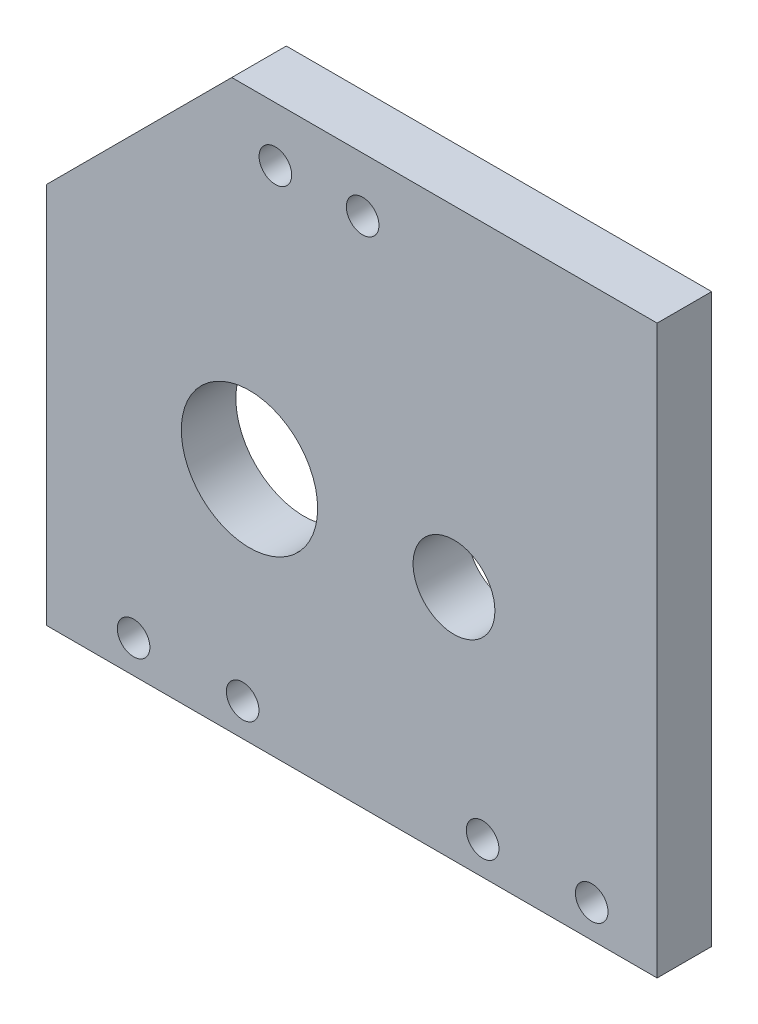
SolidWorks part; units mm, degrees
ref_plane "Front Plane" through (0, 0, 0) normal (0, 0, 1) x (1, 0, 0)
ref_plane "Top Plane" through (0, 0, 0) normal (0, 1, 0) x (1, 0, 0)
ref_plane "Right Plane" through (0, 0, 0) normal (1, 0, 0) x (0, 0, -1)
sketch "Sketch1" plane through (0, 0, 0) normal (0, 0, 1) x (1, 0, 0)
  line L1 (35.56, -33.02) -> (-35.56, -33.02)
  line L2 (35.56, -33.02) -> (35.56, 33.02)
  line L3 (35.56, 33.02) -> (-35.56, 33.02)
  line L4 (-35.56, -33.02) -> (-35.56, 33.02)
  line L5 (35.56, -33.02) -> (-35.56, 33.02) construction
  line L6 (35.56, 33.02) -> (-35.56, -33.02) construction
  circle A2 centre (-11.9062, -5.4381) radius 7.9375
  circle A3 centre (11.9062, -5.4381) radius 4.7625
  point P0 (0, 0)
  dimension "D11" = 9.525
  dimension "D12" = 15.875
  dimension "D1" = 71.12
  dimension "D2" = 66.04
  dimension "D9" = 5.4381
  dimension "D10" = 5.4381
  dimension "D13" = 11.9062
  dimension "D14" = 11.9062
extrude "Boss-Extrude1" add sketch "Sketch1" along normal blind 6.35
hole_wizard "#6 Clearance Hole1" positions "Sketch2" profile "Sketch3" hole size "#6" standard "ANSI Inch" end condition through all
sketch "Sketch2" plane through (0, 0, 6.35) normal (0, 0, 1) x (1, 0, 0)
  line L0 (-25.4, -29.21) -> (-12.7, -29.21)
  line L2 (15.24, -29.21) -> (27.94, -29.21)
  line L4 (-35.56, -33.02) -> (35.56, -33.02) construction
  line L5 (-35.56, 33.02) -> (-35.56, -33.02) construction
  point P0 (-25.4, -29.21)
  point P2 (-12.7, -29.21)
  point P4 (15.24, -29.21)
  point P6 (27.94, -29.21)
  dimension "D1" = 12.7
  dimension "D2" = 12.7
  dimension "D3" = 3.81
  dimension "D4" = 3.81
  dimension "D5" = 10.16
  dimension "D6" = 27.94
sketch "Sketch3" plane through (-25.4, -29.21, 6.35) normal (1, 0, 0) x (0, -1, 0)
  line L0 (0, 0) -> (0, 6.35)
  line L1 (0, 6.35) -> (1.8986, 6.35)
  line L2 (1.8986, 6.35) -> (1.8986, 0)
  line L5 (1.8986, 0) -> (0, 0)
  line L11 (0, -6.35) -> (0, 107.95) construction
  dimension "Thru Hole Dia." = 3.7973
  dimension "Thru Hole Depth" = 6.35
sketch "Sketch4" plane through (0, 0, 6.35) normal (0, 0, 1) x (1, 0, 0)
  line L0 (-35.56, 11.43) -> (-35.56, 33.02)
  line L1 (-35.56, 33.02) -> (-35.56, -33.02) construction
  line L2 (-35.56, 33.02) -> (-13.97, 33.02)
  line L3 (35.56, 33.02) -> (-35.56, 33.02) construction
  line L4 (-13.97, 33.02) -> (-35.56, 11.43)
  dimension "D1" = 21.59
  dimension "D2" = 21.59
extrude "Cut-Extrude1" cut sketch "Sketch4" against normal through all
hole_wizard "#6 Clearance Hole2" positions "Sketch5" profile "Sketch6" hole size "#6" standard "ANSI Inch" end condition through all
sketch "Sketch5" plane through (0, 0, 6.35) normal (0, 0, 1) x (1, 0, 0)
  line L0 (-8.89, 26.67) -> (1.27, 26.67)
  line L2 (35.56, 33.02) -> (-13.97, 33.02) construction
  point P0 (-8.89, 26.67)
  point P2 (1.27, 26.67)
  dimension "D1" = 10.16
  dimension "D2" = 6.35
  dimension "D3" = 5.08
sketch "Sketch6" plane through (-8.89, 26.67, 6.35) normal (1, 0, 0) x (0, -1, 0)
  line L0 (0, 0) -> (0, 6.35)
  line L1 (0, 6.35) -> (1.8986, 6.35)
  line L2 (1.8986, 6.35) -> (1.8986, 0)
  line L5 (1.8986, 0) -> (0, 0)
  line L11 (0, -6.35) -> (0, 107.95) construction
  dimension "Thru Hole Dia." = 3.7973
  dimension "Thru Hole Depth" = 6.35
